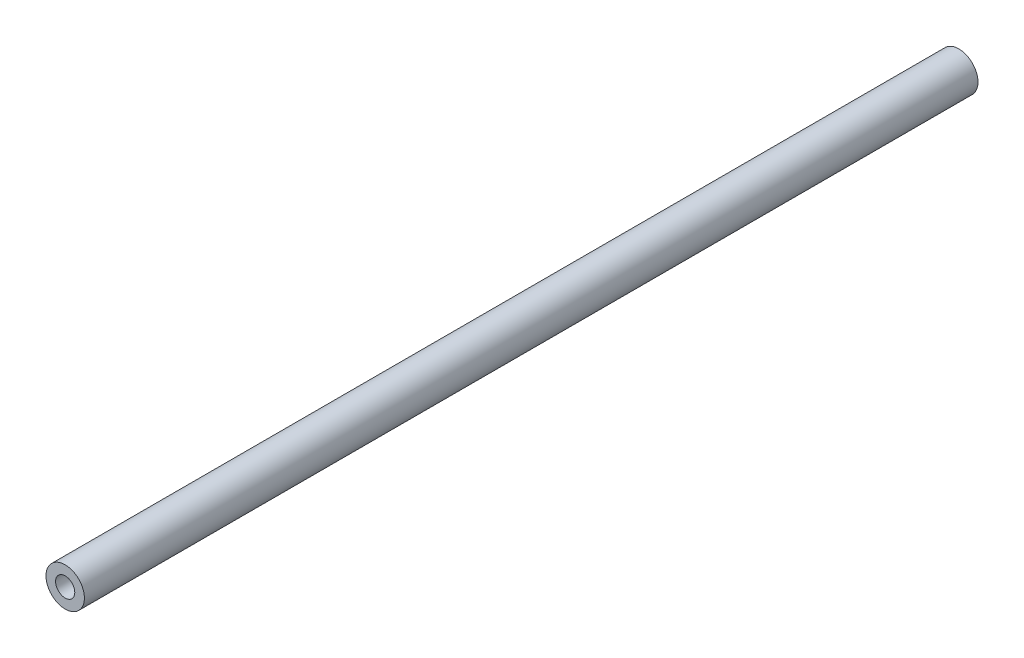
SolidWorks part; units mm, degrees
material "CFRP_TUBE_1550_DENSITY_ONLY_PROVISIONAL"
ref_plane "Front Plane" through (0, 0, 0) normal (0, 0, 1) x (1, 0, 0)
ref_plane "Top Plane" through (0, 0, 0) normal (0, 1, 0) x (1, 0, 0)
ref_plane "Right Plane" through (0, 0, 0) normal (1, 0, 0) x (0, 0, -1)
sketch "Sketch1" plane through (0, 0, 0) normal (0, 0, 1) x (1, 0, 0)
  circle A0 centre (0, 0) radius 1
  circle A1 centre (0, 0) radius 0.5
extrude "Carbon_Tube_RevB" add sketch "Sketch1" along normal blind 46.5267 from offset 23.2633
